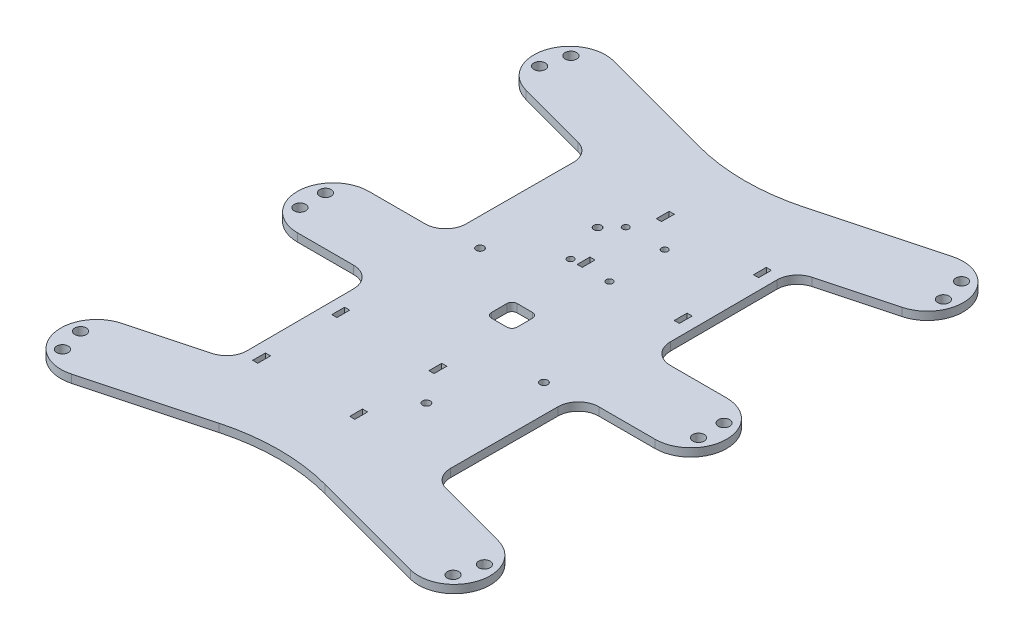
SolidWorks part; units mm, degrees
ref_plane "Front Plane" through (0, 0, 0) normal (0, 0, 1) x (1, 0, 0)
ref_plane "Top Plane" through (0, 0, 0) normal (0, 1, 0) x (1, 0, 0)
ref_plane "Right Plane" through (0, 0, 0) normal (1, 0, 0) x (0, 0, -1)
sketch "Sketch1" plane through (0, 0, 0) normal (0, 1, 0) x (1, 0, 0)
  line L0 (0, 32.1883) -> (0, -21.4181) construction
  line L1 (0, 0) -> (27.1703, 0) construction
  line L2 (-70, 14) -> (-40, 14)
  line L3 (-40, 14) -> (-39.8161, 70)
  line L4 (-39.8161, 70) -> (-73.6235, 79.0587)
  line L5 (-66.3765, 106.1046) -> (0, 88.3191)
  line L10 (-66.3765, 106.1046) -> (-73.6235, 79.0587) construction
  line L12 (-70, 14) -> (-70, -14) construction
  line L14 (-66.3765, -106.1046) -> (0, -88.3191)
  line L15 (-39.8161, -70) -> (-73.6235, -79.0587)
  line L16 (-40, -14) -> (-39.8161, -70)
  line L17 (-70, -14) -> (-40, -14)
  line L18 (66.3765, -106.1046) -> (0, -88.3191)
  line L19 (66.3765, 106.1046) -> (0, 88.3191)
  line L20 (70, 14) -> (70, -14) construction
  line L21 (66.3765, 106.1046) -> (73.6235, 79.0587) construction
  line L22 (70, -14) -> (40, -14)
  line L23 (40, -14) -> (39.8161, -70)
  line L24 (39.8161, -70) -> (73.6235, -79.0587)
  line L25 (39.8161, 70) -> (73.6235, 79.0587)
  line L26 (40, 14) -> (39.8161, 70)
  line L27 (70, 14) -> (40, 14)
  arc A0 (-70, 14) -> (-70, -14) centre (-70, 0) ccw
  arc A1 (-66.3765, 106.1046) -> (-73.6235, 79.0587) centre (-70, 92.5816) ccw
  arc A11 (-66.3765, -106.1046) -> (-73.6235, -79.0587) centre (-70, -92.5816) cw
  arc A18 (66.3765, -106.1046) -> (73.6235, -79.0587) centre (70, -92.5816) ccw
  arc A22 (66.3765, 106.1046) -> (73.6235, 79.0587) centre (70, 92.5816) cw
  arc A23 (70, 14) -> (70, -14) centre (70, 0) cw
  point P118 (-83.523, 96.2051)
  dimension "D2" = 14
  dimension "D3" = 70
  dimension "D1" = 75
  dimension "D5" = 30
  dimension "D6" = 35
  dimension "D7" = 56
extrude "Boss-Extrude1" add sketch "Sketch1" along normal blind 3.175
fillet "Fillet1" radius 80 2 edges at (0, 1.5875, -88.3191) (0, 1.5875, 88.3191)
fillet "Fillet2" radius 8 8 edges at (39.8161, 1.5875, 70) (40, 1.5875, 14) (40, 1.5875, -14) (39.8161, 1.5875, -70) (-39.8161, 1.5875, -70) (-40, 1.5875, -14) (-40, 1.5875, 14) (-39.8161, 1.5875, 70)
sketch "Sketch7" plane through (0, 3.175, 0) normal (0, 1, 0) x (1, 0, 0)
  circle A0 centre (-76.4333, -99.4818) radius 2.25 construction
  circle A1 centre (-79.0215, -89.8226) radius 2.25 construction
  circle A2 centre (-78, -5) radius 2.25 construction
  circle A3 centre (-78, 5) radius 2.25 construction
  circle A4 centre (-79.0215, 89.8226) radius 2.25 construction
  circle A5 centre (-76.4333, 99.4818) radius 2.25 construction
  circle A6 centre (79.0215, 89.8226) radius 2.25 construction
  circle A7 centre (76.4333, 99.4818) radius 2.25 construction
  circle A8 centre (78, -5) radius 2.25 construction
  circle A9 centre (78, 5) radius 2.25 construction
  circle A10 centre (79.0215, -89.8226) radius 2.25 construction
  circle A11 centre (76.4333, -99.4818) radius 2.25 construction
  circle A12 centre (-76.4333, -99.4818) radius 2.25
  circle A13 centre (-79.0215, -89.8226) radius 2.25
  circle A14 centre (-78, -5) radius 2.25
  circle A15 centre (-78, 5) radius 2.25
  circle A16 centre (-79.0215, 89.8226) radius 2.25
  circle A17 centre (-76.4333, 99.4818) radius 2.25
  circle A18 centre (79.0215, 89.8226) radius 2.25
  circle A19 centre (76.4333, 99.4818) radius 2.25
  circle A20 centre (78, -5) radius 2.25
  circle A21 centre (78, 5) radius 2.25
  circle A22 centre (79.0215, -89.8226) radius 2.25
  circle A23 centre (76.4333, -99.4818) radius 2.25
extrude "Cut-Extrude4" cut sketch "Sketch7" against normal blind 10
sketch "Sketch8" plane through (0, 3.175, 0) normal (0, 1, 0) x (1, 0, 0)
  arc A0 (13, -45) -> (13, -48) centre (13, -46.5) ccw construction
  arc A1 (13, -48) -> (13, -45) centre (13, -46.5) ccw construction
  arc A2 (29, -15) -> (29, -18) centre (29, -16.5) ccw construction
  arc A3 (29, -18) -> (29, -15) centre (29, -16.5) ccw construction
  arc A4 (-13, 48) -> (-13, 45) centre (-13, 46.5) ccw construction
  arc A5 (-13, 45) -> (-13, 48) centre (-13, 46.5) ccw construction
  arc A6 (-29, 18) -> (-29, 15) centre (-29, 16.5) ccw construction
  arc A7 (-29, 15) -> (-29, 18) centre (-29, 16.5) ccw construction
  arc A8 (13, -45) -> (13, -48) centre (13, -46.5) ccw
  arc A9 (13, -48) -> (13, -45) centre (13, -46.5) ccw
  arc A10 (29, -15) -> (29, -18) centre (29, -16.5) ccw
  arc A11 (29, -18) -> (29, -15) centre (29, -16.5) ccw
  arc A12 (-13, 48) -> (-13, 45) centre (-13, 46.5) ccw
  arc A13 (-13, 45) -> (-13, 48) centre (-13, 46.5) ccw
  arc A14 (-29, 18) -> (-29, 15) centre (-29, 16.5) ccw
  arc A15 (-29, 15) -> (-29, 18) centre (-29, 16.5) ccw
extrude "Cut-Extrude5" cut sketch "Sketch8" against normal blind 10
sketch "Sketch9" plane through (0, 3.175, 0) normal (0, 1, 0) x (1, 0, 0)
  line L0 (84, 0) -> (-84, 0) construction
  line L1 (0, 91.1411) -> (0, -91.1411) construction
  line L3 (5, 5) -> (-5, 5)
  line L4 (5, 5) -> (5, -5)
  line L5 (5, -5) -> (-5, -5)
  line L6 (-5, 5) -> (-5, -5)
  line L7 (5, 5) -> (-5, -5) construction
  line L8 (5, -5) -> (-5, 5) construction
  arc A0 (70, -14) -> (70, 14) centre (70, 0) ccw construction
  arc A1 (-70, 14) -> (-70, -14) centre (-70, 0) ccw construction
  arc A2 (-20.7055, 93.8671) -> (20.7055, 93.8671) centre (0, 171.1411) ccw construction
  arc A3 (20.7055, -93.8671) -> (-20.7055, -93.8671) centre (0, -171.1411) ccw construction
  point P16 (0, 0)
  dimension "D1" = 10
  dimension "D2" = 10
extrude "Cut-Extrude6" cut sketch "Sketch9" against normal blind 10
fillet "Fillet3" radius 2 4 edges at (5, 1.5875, -5) (-5, 1.5875, -5) (-5, 1.5875, 5) (5, 1.5875, 5)
sketch "Sketch12" plane through (0, 3.175, 0) normal (0, 1, 0) x (1, 0, 0)
  line L1 (-15.5, -92.6571) -> (-15.5, 92.6571) construction
  line L2 (0, 91.1411) -> (0, -91.1411) construction
  line L3 (-84, 0) -> (84, 0) construction
  line L4 (-35.5, -30) -> (-33.5, -30)
  line L5 (-35.5, -30) -> (-35.5, -35)
  line L6 (-35.5, -35) -> (-33.5, -35)
  line L7 (-33.5, -30) -> (-33.5, -35)
  line L8 (-35.5, -61) -> (-33.5, -61)
  line L9 (-35.5, -61) -> (-35.5, -66)
  line L10 (-35.5, -66) -> (-33.5, -66)
  line L11 (-33.5, -61) -> (-33.5, -66)
  line L12 (2.5, -61) -> (2.5, -66)
  line L13 (4.5, -66) -> (2.5, -66)
  line L14 (4.5, -61) -> (4.5, -66)
  line L15 (4.5, -61) -> (2.5, -61)
  line L16 (2.5, -30) -> (2.5, -35)
  line L17 (4.5, -35) -> (2.5, -35)
  line L18 (4.5, -30) -> (4.5, -35)
  line L19 (4.5, -30) -> (2.5, -30)
  line L36 (-2.5, 61) -> (-2.5, 66)
  line L37 (-4.5, 66) -> (-2.5, 66)
  line L38 (-4.5, 61) -> (-4.5, 66)
  line L39 (-4.5, 61) -> (-2.5, 61)
  line L40 (-2.5, 30) -> (-2.5, 35)
  line L41 (-4.5, 35) -> (-2.5, 35)
  line L42 (-4.5, 30) -> (-4.5, 35)
  line L43 (-4.5, 30) -> (-2.5, 30)
  line L44 (35.5, 30) -> (33.5, 30)
  line L45 (35.5, 30) -> (35.5, 35)
  line L46 (35.5, 35) -> (33.5, 35)
  line L47 (33.5, 30) -> (33.5, 35)
  line L48 (35.5, 61) -> (33.5, 61)
  line L49 (35.5, 61) -> (35.5, 66)
  line L50 (35.5, 66) -> (33.5, 66)
  line L51 (33.5, 61) -> (33.5, 66)
  arc A0 (20.7055, -93.8671) -> (-20.7055, -93.8671) centre (0, -171.1411) ccw construction
  arc A1 (-20.7055, 93.8671) -> (20.7055, 93.8671) centre (0, 171.1411) ccw construction
  arc A2 (-70, 14) -> (-70, -14) centre (-70, 0) ccw construction
  arc A3 (70, -14) -> (70, 14) centre (70, 0) ccw construction
  dimension "D1" = 15.5
  dimension "D2" = 26
  dimension "D3" = 2
  dimension "D4" = 5
  dimension "D5" = 18
  dimension "D6" = 30
extrude "Cut-Extrude7" cut sketch "Sketch12" against normal blind 10
sketch "Sketch13" plane through (0, 3.175, 0) normal (0, 1, 0) x (1, 0, 0)
  circle A0 centre (-7.62, 30.54) radius 1.25 construction
  circle A1 centre (-7.62, 52.13) radius 1.25 construction
  circle A2 centre (7.62, 52.13) radius 1.25 construction
  circle A3 centre (7.62, 30.54) radius 1.25 construction
  circle A4 centre (-7.62, 30.54) radius 1.25
  circle A5 centre (-7.62, 52.13) radius 1.25
  circle A6 centre (7.62, 52.13) radius 1.25
  circle A7 centre (7.62, 30.54) radius 1.25
extrude "Cut-Extrude8" cut sketch "Sketch13" against normal blind 10
